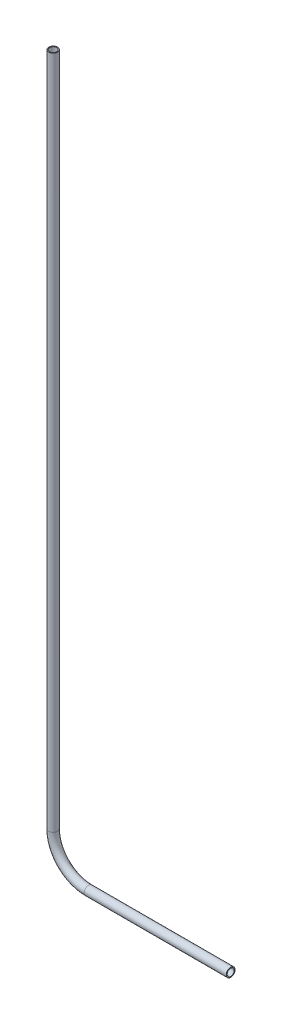
SolidWorks part; units mm, degrees
ref_plane "Front Plane" through (0, 0, 0) normal (0, 0, 1) x (1, 0, 0)
ref_plane "Top Plane" through (0, 0, 0) normal (0, 1, 0) x (1, 0, 0)
ref_plane "Right Plane" through (0, 0, 0) normal (1, 0, 0) x (0, 0, -1)
sketch "Sketch1" plane through (0, 0, 0) normal (0, 0, 1) x (1, 0, 0)
  line L0 (0, -76.2) -> (0, -558.8)
  line L1 (25.4, -584.2) -> (127, -584.2)
  arc A0 (25.4, -584.2) -> (0, -558.8) centre (25.4, -558.8) cw
  dimension "D1" = 25.4
  dimension "D2" = 482.6
  dimension "D3" = 76.2
  dimension "D4" = 101.6
ref_plane "Plane1" through (0, -76.2, 0) normal (0, -1, 0) x (-1, 0, 0)
sketch "Sketch2" plane through (0, -76.2, 0) normal (0, -1, 0) x (-1, 0, 0)
  circle A0 centre (0, 0) radius 3.175
  circle A1 centre (0, 0) radius 2.54
  dimension "D1" = 6.35
  dimension "D2" = 0.635
sweep "Sweep1" add profiles "Sketch2" path "Sketch1"
